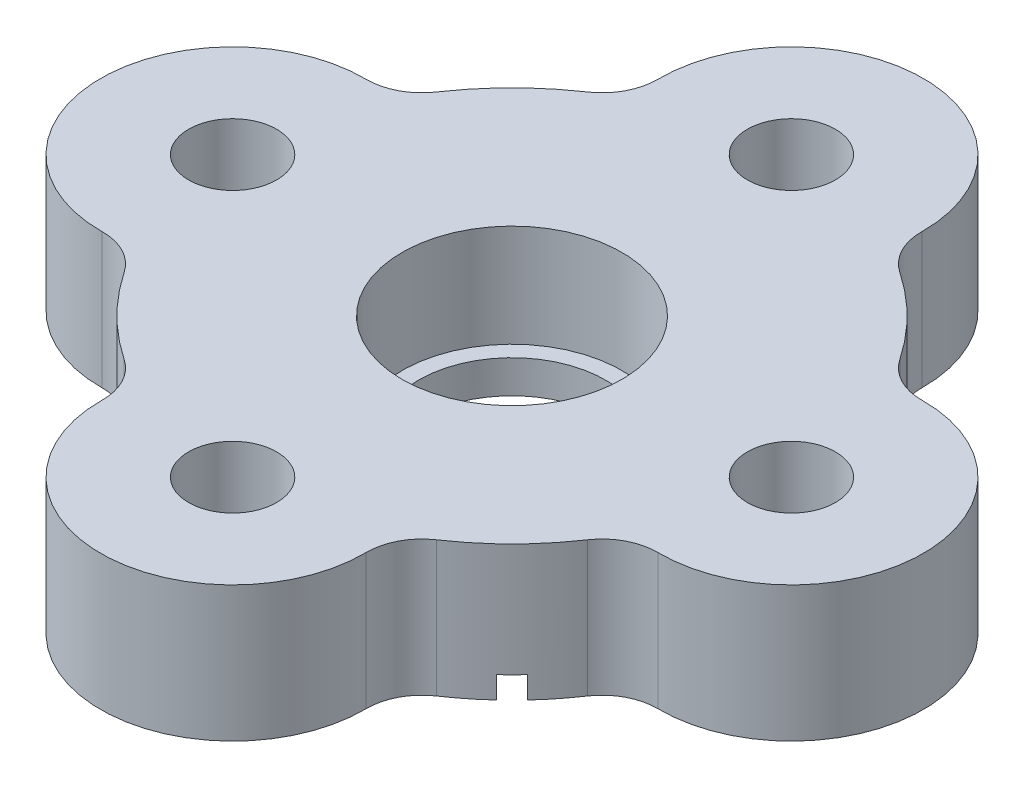
SolidWorks part; units mm, degrees
material "1060 Alloy"
ref_plane "Front" through (0, 0, 0) normal (0, 0, 1) x (1, 0, 0)
ref_plane "Top" through (0, 0, 0) normal (0, 1, 0) x (1, 0, 0)
ref_plane "Right" through (0, 0, 0) normal (1, 0, 0) x (0, 0, -1)
sketch "Sketch1" plane through (0, 0, 0) normal (0, 1, 0) x (1, 0, 0)
  line L0 (0, 0) -> (0, 44.45) construction
  circle A0 centre (-25.4, 0) radius 4
  circle A1 centre (0, 25.4) radius 4
  circle A2 centre (25.4, 0) radius 4
  circle A3 centre (0, -25.4) radius 4
  circle A4 centre (0, 0) radius 8.5
  arc A6 (11.9992, 25.261) -> (-11.9992, 25.261) centre (0, 25.4) ccw
  arc A7 (25.261, -11.9992) -> (25.261, 11.9992) centre (25.4, 0) ccw
  arc A8 (-11.9992, -25.261) -> (11.9992, -25.261) centre (0, -25.4) ccw
  arc A9 (-25.261, 11.9992) -> (-25.261, -11.9992) centre (-25.4, 0) ccw
  arc A10 (-14.203, 21.0579) -> (-21.0579, 14.203) centre (0, 0) ccw
  arc A11 (-21.0579, -14.203) -> (-14.203, -21.0579) centre (0, 0) ccw
  arc A12 (14.203, -21.0579) -> (21.0579, -14.203) centre (0, 0) ccw
  arc A13 (21.0579, 14.203) -> (14.203, 21.0579) centre (0, 0) ccw
  arc A14 (14.203, 21.0579) -> (11.9992, 25.261) centre (16.9989, 25.2031) cw
  arc A15 (25.261, 11.9992) -> (21.0579, 14.203) centre (25.2031, 16.9989) cw
  arc A16 (25.261, -11.9992) -> (21.0579, -14.203) centre (25.2031, -16.9989) ccw
  arc A17 (11.9992, -25.261) -> (14.203, -21.0579) centre (16.9989, -25.2031) cw
  arc A18 (-11.9992, -25.261) -> (-14.203, -21.0579) centre (-16.9989, -25.2031) ccw
  arc A19 (-25.261, -11.9992) -> (-21.0579, -14.203) centre (-25.2031, -16.9989) cw
  arc A20 (-25.261, 11.9992) -> (-21.0579, 14.203) centre (-25.2031, 16.9989) ccw
  arc A21 (-14.203, 21.0579) -> (-11.9992, 25.261) centre (-16.9989, 25.2031) ccw
  point P0 (0, 0)
  point P17 (0, 0)
  point P25 (0, 0)
  point P30 (22.5654, 11.6604)
  point P33 (22.5654, -11.6604)
  point P36 (11.6604, -22.5654)
  point P39 (-11.6604, -22.5654)
  point P42 (-22.5654, -11.6604)
  dimension "D5" = 8
  dimension "D6" = 17
  dimension "D3" = 24
  dimension "D8" = 5
  dimension "D2" = 50.8
  dimension "D4" = 4
  dimension "D7" = 4
extrude "body and center hole" add sketch "Sketch1" along normal blind 12.3
sketch "Sketch2" plane through (0, 12.3, 0) normal (0, 1, 0) x (1, 0, 0)
  circle A0 centre (0, 0) radius 10
  dimension "D1" = 20
extrude "seal bore" cut sketch "Sketch2" against normal blind 9.3
sketch "Sketch3" plane through (0, 0, 0) normal (0, -1, 0) x (1, 0, 0)
  line L0 (0, 0) -> (17.9605, 17.9605) construction
  line L2 (36.6281, 35.2139) -> (35.2139, 36.6281)
  line L3 (36.6281, 35.2139) -> (0.7071, -0.7071)
  line L4 (0.7071, -0.7071) -> (-0.7071, 0.7071)
  line L5 (35.2139, 36.6281) -> (-0.7071, 0.7071)
  line L6 (36.6281, 35.2139) -> (-0.7071, 0.7071) construction
  line L7 (0.7071, -0.7071) -> (35.2139, 36.6281) construction
  arc A0 (21.0579, 14.203) -> (14.203, 21.0579) centre (0, 0) ccw construction
  point P6 (17.9605, 17.9605)
  dimension "D1" = 2
extrude "vent" cut sketch "Sketch3" against normal blind 2
equation "\"D2@Sketch1\"=\"square plate bolt pattern diameter\""
equation "\"D5@Sketch1\"=\"square plate bolt hole ID\""
equation "\"D1@body and center hole\"=\"small seal plate thickness\""
equation "\"D6@Sketch1\"=\"small seal plate lip ID\""
equation "\"D1@Sketch2\"=\"small seal OD\""
equation "\"D1@seal bore\" = \"small seal bore\""
equation "\"bearing OD\" = 30mm"
equation "\"bearing outer race thickness\"= 1mm"
equation "\"bearing ID\"= 10mm"
equation "\"bearing depth\"= 9mm"
equation "\"bearing inner race thickness\"= 1mm"
equation "\"small seal OD\" = 20mm"
equation "\"small seal ID\"= 8mm"
equation "\"small seal depth\" = 8.3mm"
equation "\"big seal OD\" = 27mm"
equation "\"big seal ID\"= 15mm"
equation "\"big seal depth\"= 8.3mm"
equation "\"z\" = 8 \t\t\t\t'number of blades"
equation "\"de\" = 0.426in \t\t\t\t'entrance eye diameter"
equation "\"d2\" = 2.097in \t\t\t\t'outer diameter of the impeller "
equation "\"d_exit\" = 0.18in \t\t\t'volute throat aka D4"
equation "\"theta\" = 15"
equation "\"b2\" = .071in\t\t\t\t\t\t\t\t'tip height from disc surface at d2"
equation "\"b1\" = \"b2\" + (\"d2\"/2 - \"de\"/2)*sin(\"theta\")\t\t\t\t'tip height from disc surface at inlet eye"
equation "\"s\" = ( 1/\"z\")*(3.14*\"de\" - (3.14*(\"de\"^2) / (4*(\"b1\"))))\t\t'thickness of blades, calculated from area"
equation "\"s_opening\" = (3.14*\"de\" - \"z\"*\"s\")/\"z\"\t\t\t\t\t'ideal gap between blades, calculated from area"
equation "\"area_eye\"=3.14*(\"de\"^2)/4\t\t\t\t\t\t'eye area"
equation "\"single_channel_area\"=\"s_opening\"*\"b1\"\t\t\t\t\t'ideal area between two blades"
equation "\"impeller upper clearance\"= .5mm"
equation "\"impeller horizontal clearance\"= (\"d2\"*1.15 - \"d2\")/2 \t\t\t\t\t'clearance based on D2-D3 ratio for circular volute, ranges 1.15 to 1.2"
equation "\"impeller bottom clearance\"= .5mm"
equation "\"impeller base thickness\"= 2mm"
equation "\"impeller boss depth\" = \"shaft impeller section length\" + 3mm + \"impeller bolt head depth\" - \"impeller base thickness\""
equation "\"impeller boss diameter\" = \"big seal ID\""
equation "\"impeller dowel diameter\" = 2mm"
equation "\"impeller bolt head diameter\" = 7.5mm"
equation "\"impeller bolt head depth\" = 4mm"
equation "\"impeller shaft bore\"= 8mm"
equation "\"impeller shaft bore depth\" = \"impeller boss depth\" + \"impeller base thickness\" - \"impeller bolt head depth\" - 3mm"
equation "\"impeller dowel length\" = 2mm*2 + \"impeller shaft bore\""
equation "\"impeller screw hole bore\" = 4mm"
equation "\"shaft impeller screw hole diameter\" = \"impeller screw hole bore\""
equation "\"shaft impeller section length\" = \"big seal plate thickness\"/2 + \"impeller bottom clearance\" + \"impeller base thickness\" - \"impeller bolt head depth\" - 3mm"
equation "\"shaft impeller screw hole depth\" = \"shaft impeller section length\"-\"impeller dowel diameter\"-2mm"
equation "\"shaft impeller section diameter\" = \"impeller shaft bore\""
equation "\"shaft seal section diameter\"=\"small seal ID\""
equation "\"shaft seal section length\"= \"big seal plate thickness\"/2 + \"small seal bore\" + 2mm"
equation "\"shaft bearing section diameter\" = \"bearing ID\""
equation "\"shaft bearing section length\" = \"bearing bore\""
equation "\"shaft bearing stop diameter\" = \"bearing ID\" + 2mm"
equation "\"shaft bearing stop length\" = 2mm"
equation "\"shaft coupler section diameter\" = 8mm"
equation "\"shaft coupler section length\" = \"shaft bearing stop length\" + \"coupler length\"/2 + 4mm"
equation "\"coupler motor shaft hole ID\"= 8mm"
equation "\"coupler OD\"= 17mm"
equation "\"coupler length\"= 25mm"
equation "\"square plate diameter\" = 3in"
equation "\"square plate bolt pattern diameter\"= 2in"
equation "\"square plate bolt hole ID\" = 8mm"
equation "\"bearing plate bearing stop ID\" = \"bearing OD\" - 4mm"
equation "\"bearing plate bearing stop depth\" = 3mm"
equation "\"bearing plate thickness\" = \"bearing bore\" + \"bearing plate bearing stop depth\""
equation "\"small seal plate lip depth\" = \"shaft bearing stop length\" + 1mm"
equation "\"small seal plate lip ID\" = \"small seal OD\" - 3mm"
equation "\"small seal plate thickness\" = \"small seal plate lip depth\" + \"small seal bore\""
equation "\"big seal plate lip depth\" = 8mm"
equation "\"big seal plate thickness\" = \"big seal plate outer thickness\" + \"big seal plate riser height\""
equation "\"impeller cavity center height\"= \"impeller bottom clearance\" + \"impeller upper clearance\" + \"final impeller center height\""
equation "\"impeller cavity diameter\"= 2 * \"impeller horizontal clearance\" + \"d2\" \t\t\t'called D3 analytically"
equation "\"impeller cavity outer height\"= \"impeller bottom clearance\" + \"impeller upper clearance\" + \"impeller base thickness\" + \"b2\" \t\t\t'this is height at impeller diameter d2, not at d3"
equation "\"impeller housing bolt count\" = 8"
equation "\"impeller housing bolt diameter\" = 6mm"
equation "\"impeller housing bolt pattern diameter\" = 3in"
equation "\"impeller housing o-ring channel height\"= 1.5mm"
equation "\"impeller housing o ring channel width\"= 1.5mm"
equation "\"impeller housing o-ring diameter\" = 2in"
equation "\"impeller housing threaded inlet diameter\" = 0.6875in \t\t\t'this is the 11/16 drill size for 1/2 npt fitting"
equation "\"impeller housing threaded inlet depth\"= 20mm"
equation "\"impeller housing thickness\"= \"impeller housing exit threaded diameter\" + 2*\"impeller housing outlet purchase\""
equation "\"impeller housing exit threaded diameter\"= 0.6875in \t\t\t'this is the 11/16 drill size for 1/2 npt fitting"
equation "\"impeller housing exit threaded depth\"= 12mm"
equation "\"impeller housing diameter\" = 4in"
equation "\"impeller housing diffuser conical angle\"=10"
equation "\"impeller housing diffuser tangent angle\"=0"
equation "\"impeller housing outlet purchase\" = 6mm"
equation "\"motor to housing distance\" = \"motor shaft pride\" + \"shaft coupler section length\" - \"bearing plate bearing stop depth\" + 2mm"
equation "\"motor mount coupler hole diameter\"= \"coupler OD\"+ 4mm"
equation "\"motor mount to housing post radius\"= ( 3 * \"square plate bolt hole ID\" ) / 2"
equation "\"motor mount m4 screw hole diameter\"= 4mm"
equation "\"motor mount m4 head diameter\"= 7.25mm"
equation "\"motor mount m4 head depth\"= 4mm"
equation "\"motor mount plate thickness\"= 8mm + \"motor mount m4 head depth\""
equation "\"motor shaft pride\"= 32mm"
equation "\"motor shaft flat section length from tip\"= 25.7mm"
equation "\"motor shaft bore end clearance\"= 2mm"
equation "\"coupler shaft to motor clearance\" = 2mm"
equation "\"motor mount shaft hole depth\"= \"motor shaft pride\""
equation "\"D3@Sketch1\"=\"square plate bolt hole ID\"*3"
equation "\"bearing bore\" = \"bearing depth\" + 1mm"
equation "\"small seal bore\" = \"small seal depth\" + 1mm"
equation "\"big seal bore\" = \"big seal depth\" + 1mm"
equation "\"bit size\"= 1mm"
equation "\"inlet area before cut\" = \"minimum channel width\" * (\"z\") * \"b1\"\t\t\t\t'if minimum channel width>s_opening, this is larger than area_eye"
equation "\"area to cut\" = \"inlet area before cut\" - \"area_eye\"\t\t\t\t\t\t'amount of extra area\t\t\t\t\t"
equation "\"height to cut\" = \"area to cut\" / ((\"z\")* \"minimum channel width\")+ .0001in\t\t\t'the 0.0001 in cut is to avoid errors in model"
equation "\"final impeller center height\" = \"impeller base thickness\" + \"b1\" - \"height to cut\"\t\t'corrected height so that sum of channel areas equals eye area"
equation "\"big seal plate pressure hole diameter\" = .125in\t\t\t'this is 1/8 drill "
equation "\"big seal plate pressure tap diameter\" = .328125in \t\t'this is 21/64 drill for a 1/8 ANPT tap"
equation "\"big seal plate pressure tap depth\" = 9mm"
equation "\"motor mount m4 pattern diamater\" = 30mm"
